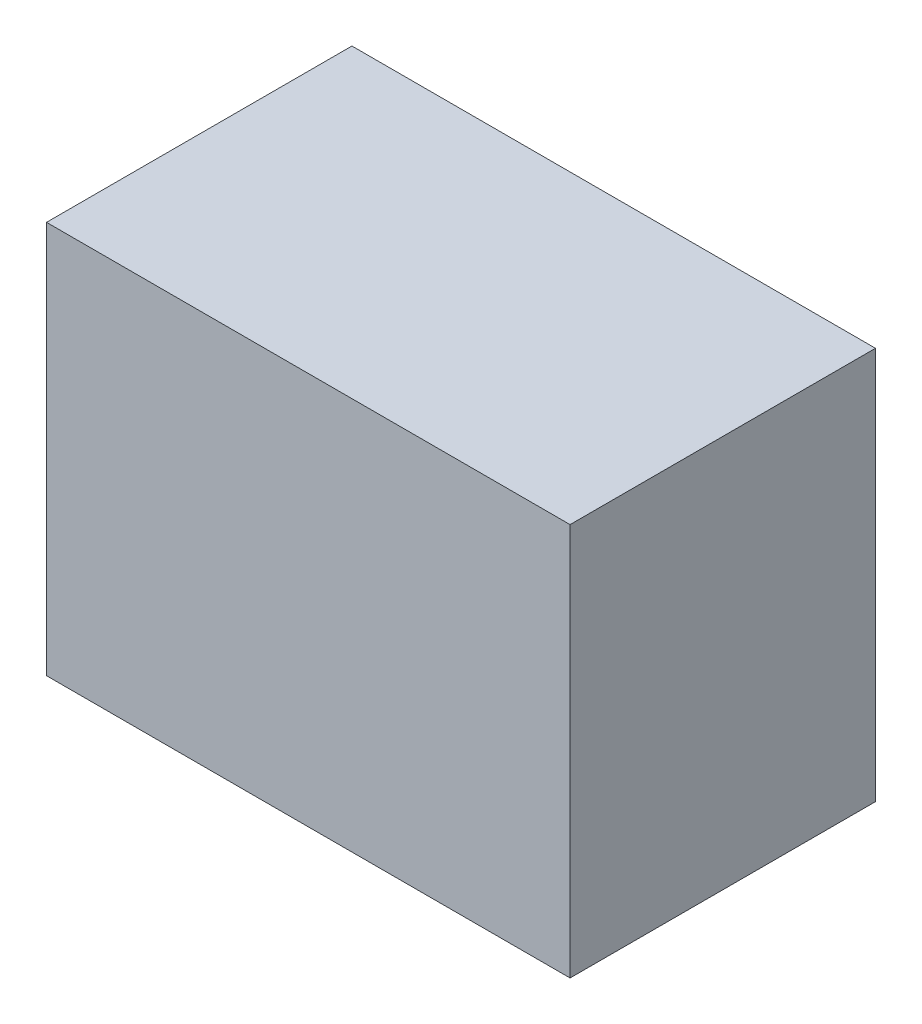
SolidWorks part; units mm, degrees
ref_plane "Front Plane" through (0, 0, 0) normal (0, 0, 1) x (1, 0, 0)
ref_plane "Top Plane" through (0, 0, 0) normal (0, 1, 0) x (1, 0, 0)
ref_plane "Right Plane" through (0, 0, 0) normal (1, 0, 0) x (0, 0, -1)
sketch "Sketch1" plane through (0, 0, 0) normal (0, 1, 0) x (1, 0, 0)
  line L1 (-152.4, -88.9) -> (152.4, -88.9)
  line L2 (-152.4, -88.9) -> (-152.4, 88.9)
  line L3 (-152.4, 88.9) -> (152.4, 88.9)
  line L4 (152.4, -88.9) -> (152.4, 88.9)
  line L5 (-152.4, -88.9) -> (152.4, 88.9) construction
  line L6 (-152.4, 88.9) -> (152.4, -88.9) construction
  point P0 (0, 0)
  dimension "D1" = 177.8
  dimension "D2" = 304.8
extrude "Boss-Extrude1" add sketch "Sketch1" along normal blind 228.6
ref_plane "Plane1" through (0, 152.4, 0) normal (0, 1, 0) x (1, 0, 0)
sketch "Sketch2" plane through (0, 152.4, 0) normal (0, 1, 0) x (1, 0, 0)
  line L0 (-152.4, 0) -> (-158.75, 0)
  line L1 (-152.4, 88.9) -> (-152.4, -88.9) construction
  line L2 (-158.75, 0) -> (-158.75, 29.1375)
  line L3 (-158.75, 29.1375) -> (-152.4, 29.1375)
  line L4 (-152.4, 29.1375) -> (-152.4, 0)
  dimension "D1" = 6.35
revolve "Revolve1" add sketch "Sketch2" angle 360 about L0
